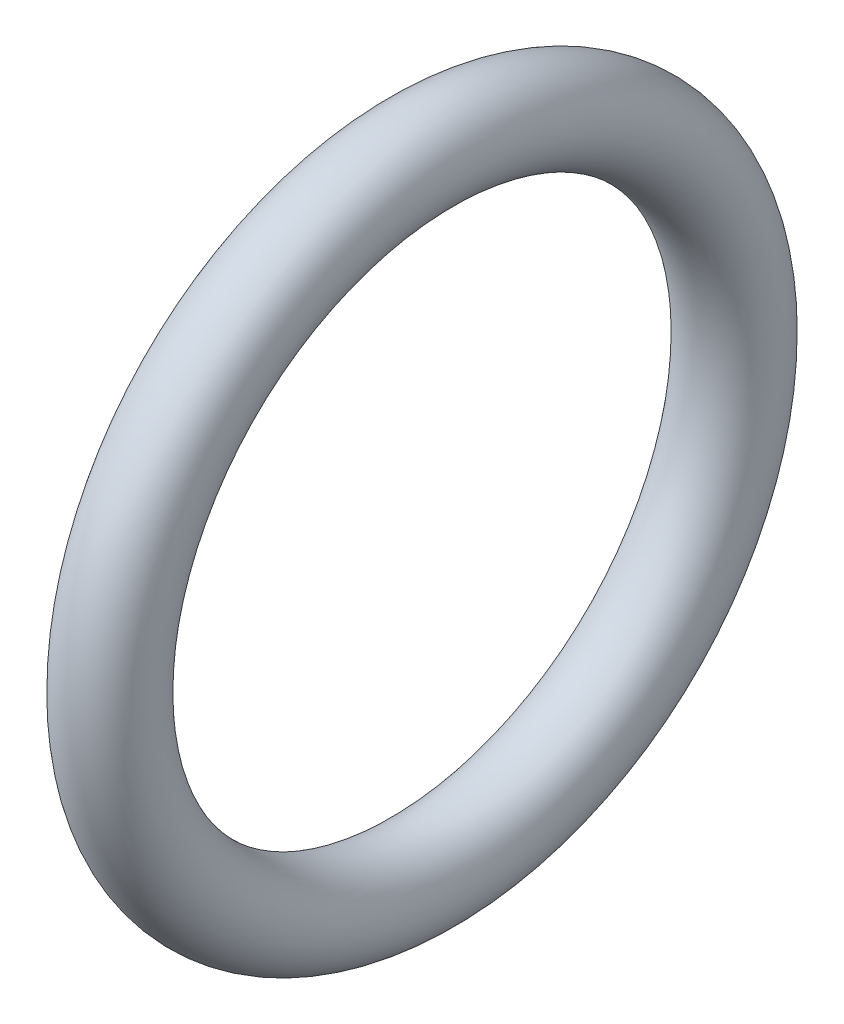
SolidWorks part; units mm, degrees
material "Rubber"
ref_plane "Front Plane" through (0, 0, 0) normal (0, 0, 1) x (1, 0, 0)
ref_plane "Top Plane" through (0, 0, 0) normal (0, 1, 0) x (1, 0, 0)
ref_plane "Right Plane" through (0, 0, 0) normal (1, 0, 0) x (0, 0, -1)
sketch "Sketch1" plane through (0, 0, 0) normal (0, 0, 1) x (1, 0, 0)
  line L0 (0, 0) -> (0, 254) construction
  circle A0 centre (0, 222.25) radius 31.75
  dimension "D2" = 63.5
  dimension "D1" = 254
ref_axis "Axis1" through (0, 0, 0) along (1, 0, 0)
revolve "Revolve1" add sketch "Sketch1" angle 360 about axis through (0, 0, 0) along (1, 0, 0)
equation "\"D1@Sketch1\"=10"
